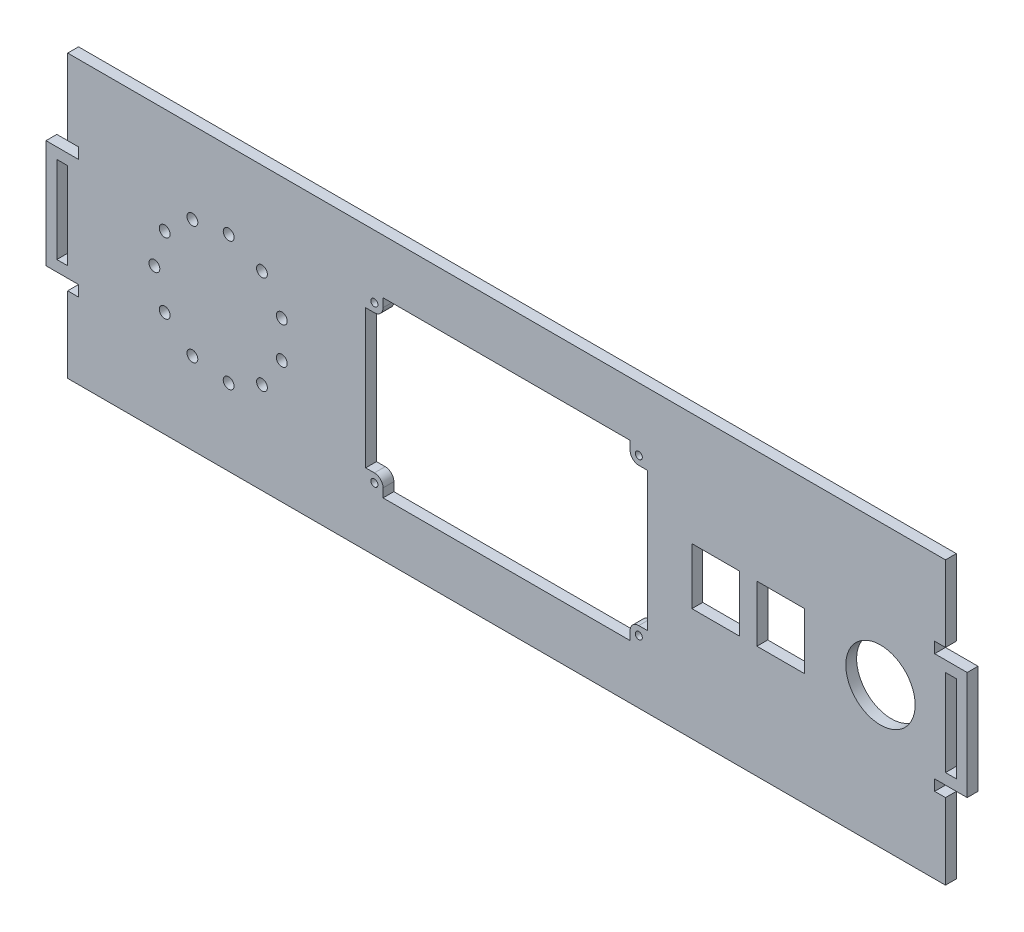
SolidWorks part; units mm, degrees
ref_plane "Front Plane" through (0, 0, 0) normal (0, 0, 1) x (1, 0, 0)
ref_plane "Top Plane" through (0, 0, 0) normal (0, 1, 0) x (1, 0, 0)
ref_plane "Right Plane" through (0, 0, 0) normal (1, 0, 0) x (0, 0, -1)
sketch "Sketch1" plane through (0, 0, 0) normal (0, 0, 1) x (1, 0, 0)
  line L1 (0, 0) -> (-180, 0)
  line L2 (0, 0) -> (0, 130)
  line L3 (0, 130) -> (-180, 130)
  line L4 (-180, 0) -> (-180, 130)
  dimension "D1" = 130
  dimension "D2" = 180
extrude "Boss-Extrude1" add sketch "Sketch1" along normal blind 5
sketch "Sketch2" plane through (0, 0, 5) normal (0, 0, 1) x (1, 0, 0)
  line L0 (0, 130) -> (-180, 130) construction
  line L1 (-155, 105) -> (-25, 105)
  line L2 (-155, 105) -> (-155, 25)
  line L3 (-155, 25) -> (-25, 25)
  line L4 (-25, 105) -> (-25, 25)
  line L5 (-180, 130) -> (-180, 0) construction
  dimension "D1" = 130
  dimension "D2" = 80
  dimension "D3" = 25
  dimension "D4" = 25
extrude "Cut-Extrude1" cut sketch "Sketch2" against normal blind 10
sketch "Sketch5" plane through (0, 0, 5) normal (0, 0, 1) x (1, 0, 0)
  line L0 (-25, 105) -> (-155, 105) construction
  line L1 (-25, 25) -> (-25, 105) construction
  line L2 (-90, 105) -> (-90, 82.7947) construction
  line L3 (-155, 65) -> (-112.6302, 65) construction
  line L4 (-155, 105) -> (-155, 25) construction
  line L5 (-33, 101) -> (-33, 105)
  line L6 (-33, 105) -> (-25, 105)
  line L7 (-25, 105) -> (-25, 97)
  line L8 (-25, 97) -> (-29, 97)
  line L9 (-155, 97) -> (-151, 97)
  line L10 (-155, 105) -> (-155, 97)
  line L11 (-147, 105) -> (-155, 105)
  line L12 (-147, 101) -> (-147, 105)
  line L13 (-25, 33) -> (-29, 33)
  line L14 (-25, 25) -> (-25, 33)
  line L15 (-33, 25) -> (-25, 25)
  line L16 (-33, 29) -> (-33, 25)
  line L17 (-147, 29) -> (-147, 25)
  line L18 (-147, 25) -> (-155, 25)
  line L19 (-155, 25) -> (-155, 33)
  line L20 (-155, 33) -> (-151, 33)
  arc A0 (-33, 101) -> (-29, 97) centre (-29, 101) ccw
  circle A1 centre (-29, 101) radius 1.625
  circle A2 centre (-151, 101) radius 1.625
  arc A3 (-147, 101) -> (-151, 97) centre (-151, 101) cw
  circle A4 centre (-29, 29) radius 1.625
  arc A5 (-33, 29) -> (-29, 33) centre (-29, 29) cw
  arc A6 (-147, 29) -> (-151, 33) centre (-151, 29) ccw
  circle A7 centre (-151, 29) radius 1.625
  dimension "D1" = 8
  dimension "D2" = 3.25
extrude "Boss-Extrude3" add sketch "Sketch5" against normal blind 5
sketch "Sketch6" plane through (0, 0, 5) normal (0, 0, 1) x (1, 0, 0)
  line L0 (-147, 25) -> (-33, 25) construction
  line L1 (-180, 130) -> (-292.5, 130)
  line L2 (-180, 130) -> (-180, 0)
  line L3 (-180, 0) -> (-292.5, 0)
  line L4 (-292.5, 130) -> (-292.5, 0)
  line L5 (-90, 130) -> (-90, 181.4808) construction
  line L6 (0, 130) -> (-180, 130) construction
  line L7 (112.5, 130) -> (112.5, 0)
  line L8 (0, 0) -> (112.5, 0)
  line L9 (0, 130) -> (0, 0)
  line L10 (0, 130) -> (112.5, 130)
  point P7 (-90, 25)
  dimension "D1" = 202.5
  dimension "D2" = 130
extrude "Boss-Extrude4" add sketch "Sketch6" against normal blind 5
sketch "Sketch7" plane through (0, 0, 5) normal (0, 0, 1) x (1, 0, 0)
  line L0 (-292.5, 130) -> (-292.5, 0) construction
  line L1 (-292.5, 35) -> (-287.5, 35)
  line L2 (-292.5, 35) -> (-292.5, 40)
  line L3 (-292.5, 40) -> (-287.5, 40)
  line L4 (-287.5, 35) -> (-287.5, 40)
  line L5 (-292.5, 0) -> (112.5, 0) construction
  line L6 (-292.5, 65) -> (-274.1532, 65) construction
  line L7 (-287.5, 95) -> (-287.5, 90)
  line L8 (-292.5, 90) -> (-287.5, 90)
  line L9 (-292.5, 95) -> (-292.5, 90)
  line L10 (-292.5, 95) -> (-287.5, 95)
  line L11 (-90, 0) -> (-90, -43.5867) construction
  line L12 (112.5, 65) -> (94.1532, 65) construction
  line L13 (112.5, 95) -> (107.5, 95)
  line L14 (112.5, 95) -> (112.5, 90)
  line L15 (112.5, 90) -> (107.5, 90)
  line L16 (107.5, 95) -> (107.5, 90)
  line L17 (107.5, 35) -> (107.5, 40)
  line L18 (112.5, 40) -> (107.5, 40)
  line L19 (112.5, 35) -> (112.5, 40)
  line L20 (112.5, 35) -> (107.5, 35)
  dimension "D1" = 5
  dimension "D2" = 5
  dimension "D3" = 35
extrude "Cut-Extrude2" cut sketch "Sketch7" against normal blind 5
sketch "Sketch8" plane through (0, 0, 5) normal (0, 0, 1) x (1, 0, 0)
  line L0 (-90, 0) -> (-90, -49.1322) construction
  line L1 (-292.5, 40) -> (-302.5, 40)
  line L2 (-292.5, 40) -> (-292.5, 90)
  line L3 (-292.5, 90) -> (-302.5, 90)
  line L4 (-302.5, 40) -> (-302.5, 90)
  line L5 (-292.5, 45) -> (-297.5, 45)
  line L6 (-292.5, 45) -> (-292.5, 85)
  line L7 (-292.5, 85) -> (-297.5, 85)
  line L8 (-297.5, 45) -> (-297.5, 85)
  line L9 (-292.5, 0) -> (112.5, 0) construction
  line L10 (117.5, 45) -> (117.5, 85)
  line L11 (112.5, 85) -> (117.5, 85)
  line L12 (112.5, 45) -> (112.5, 85)
  line L13 (112.5, 45) -> (117.5, 45)
  line L14 (122.5, 40) -> (122.5, 90)
  line L15 (112.5, 90) -> (122.5, 90)
  line L16 (112.5, 40) -> (112.5, 90)
  line L17 (112.5, 40) -> (122.5, 40)
  line M9 (112.5, 40) -> (112.5, 90)
  line M19 (-292.5, 90) -> (-292.5, 40)
  dimension "D1" = 10
  dimension "D2" = 50
  dimension "D3" = 40
  dimension "D4" = 5
  dimension "D5" = 5
extrude "Boss-Extrude5" add sketch "Sketch8" against normal blind 5 contours L5 L8 L7 L3 L4 L1 L2 M19 | L17 L14 L15 L11 L10 L13 M9
sketch "Sketch9" plane through (0, 0, 5) normal (0, 0, 1) x (1, 0, 0)
  line L0 (-292.5, 35) -> (-292.5, 0) construction
  line L1 (-292.5, 0) -> (112.5, 0) construction
  line L2 (-90, 0) -> (-90, -45.9076) construction
  circle A0 centre (-222.5, 65) radius 30 construction
  circle A1 centre (-252.5, 65) radius 2.5
  circle A2 centre (-247.7376, 81.2192) radius 2.5
  circle A3 centre (-234.9625, 92.289) radius 2.5
  circle A4 centre (-218.2306, 94.6946) radius 2.5
  circle A5 centre (-202.8542, 87.6725) radius 2.5
  circle A6 centre (-193.7152, 73.452) radius 2.5
  circle A7 centre (-193.7152, 56.548) radius 2.5
  circle A8 centre (-202.8542, 42.3275) radius 2.5
  circle A9 centre (-218.2306, 35.3054) radius 2.5
  circle A10 centre (-234.9625, 37.711) radius 2.5
  circle A11 centre (-247.7376, 48.7808) radius 2.5
  dimension "D1" = 70
  dimension "D2" = 65
  dimension "D3" = 60
  dimension "D4" = 5
  dimension "D5" = 11
extrude "Cut-Extrude3" cut sketch "Sketch9" against normal blind 5
sketch "Sketch10" plane through (0, 0, 5) normal (0, 0, 1) x (1, 0, 0)
  line L0 (-292.5, 0) -> (112.5, 0) construction
  line L1 (112.5, 95) -> (112.5, 130) construction
  line L2 (-4.5, 78) -> (-4.5, 52)
  line L3 (25.5, 78) -> (47.5, 78)
  line L4 (25.5, 78) -> (25.5, 52)
  line L5 (25.5, 52) -> (47.5, 52)
  line L6 (47.5, 78) -> (47.5, 52)
  line L7 (-4.5, 78) -> (17.5, 78)
  line L8 (17.5, 78) -> (17.5, 52)
  line L9 (-4.5, 52) -> (17.5, 52)
  circle A0 centre (82.5, 65) radius 16
  point P10 (47.5, 65)
  dimension "D1" = 32
  dimension "D3" = 30
  dimension "D2" = 65
  dimension "D4" = 22
  dimension "D5" = 26
  dimension "D6" = 35
  dimension "D7" = 2
extrude "Cut-Extrude4" cut sketch "Sketch10" against normal blind 5 contours L4 L3 L6 L5 | L2 L9 L8 L7 | A0
